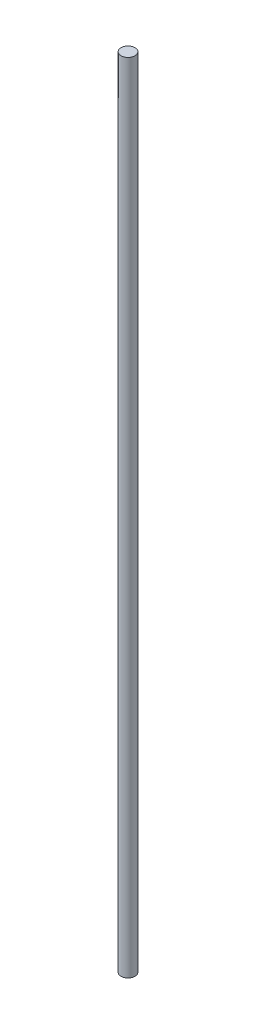
SolidWorks part; units mm, degrees
ref_plane "Front Plane" through (0, 0, 0) normal (0, 0, 1) x (1, 0, 0)
ref_plane "Top Plane" through (0, 0, 0) normal (0, 1, 0) x (1, 0, 0)
ref_plane "Right Plane" through (0, 0, 0) normal (1, 0, 0) x (0, 0, -1)
sketch "Sketch1" plane through (0, 0, 0) normal (0, 1, 0) x (1, 0, 0)
  circle A0 centre (0, 0) radius 4
  dimension "D1" = 8
extrude "Boss-Extrude1" add sketch "Sketch1" along normal blind 455.9
equation "\"d\"= 8"
equation "\"l\"= 455.9"
equation "\"D1@Boss-Extrude1\"=\"l\""
equation "\"D1@Sketch1\"=\"d\""
